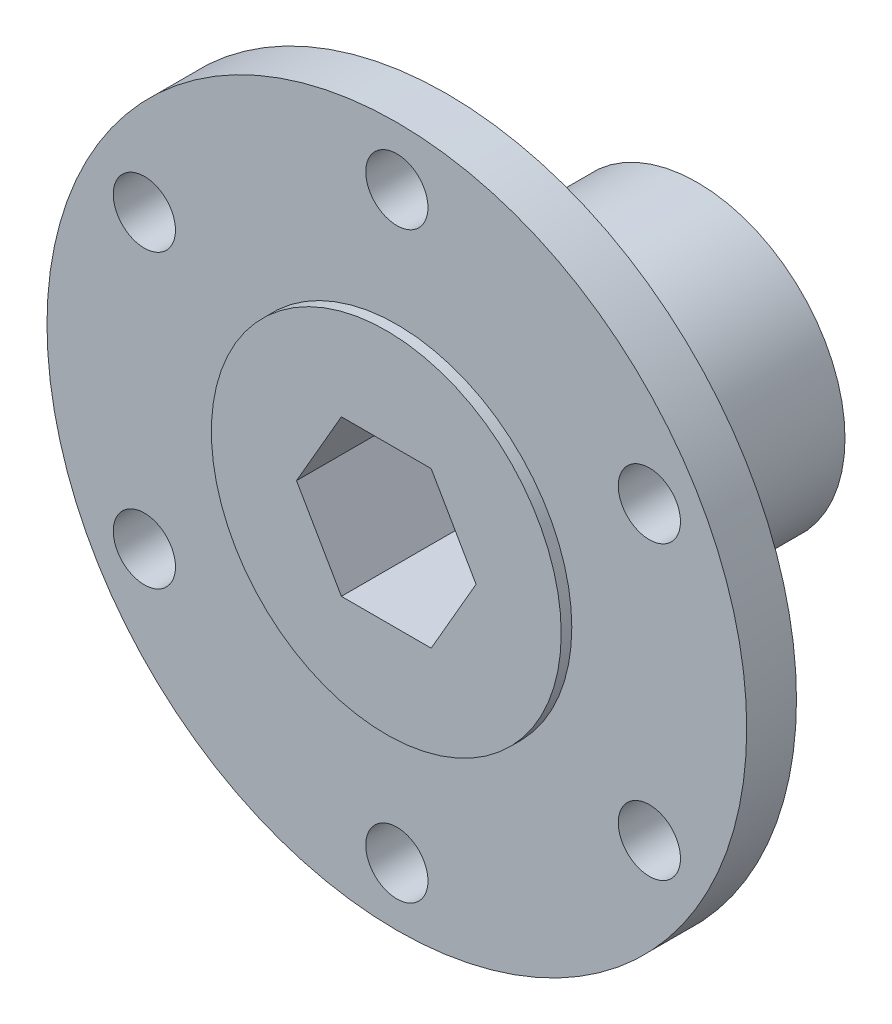
SolidWorks part; units mm, degrees
ref_plane "Front Plane" through (0, 0, 0) normal (0, 0, 1) x (1, 0, 0)
ref_plane "Top Plane" through (0, 0, 0) normal (0, 1, 0) x (1, 0, 0)
ref_plane "Right Plane" through (0, 0, 0) normal (1, 0, 0) x (0, 0, -1)
sketch "Sketch1" plane through (0, 0, 0) normal (0, 0, 1) x (1, 0, 0)
  line L0 (0, 0) -> (0, 23.8125) construction
  line L1 (7.3323, 0) -> (3.6662, 6.35)
  line L2 (3.6662, 6.35) -> (-3.6662, 6.35)
  line L3 (-3.6662, 6.35) -> (-7.3323, 0)
  line L4 (-7.3323, 0) -> (-3.6662, -6.35)
  line L5 (-3.6662, -6.35) -> (3.6662, -6.35)
  line L6 (3.6662, -6.35) -> (7.3323, 0)
  circle A0 centre (0, 0) radius 28.575
  circle A1 centre (0, 0) radius 6.35 construction
  circle A2 centre (0, 23.8125) radius 2.54
  circle A3 centre (20.6222, 11.9063) radius 2.54
  circle A4 centre (20.6222, -11.9062) radius 2.54
  circle A5 centre (0, -23.8125) radius 2.54
  circle A6 centre (-20.6222, -11.9063) radius 2.54
  circle A7 centre (-20.6222, 11.9062) radius 2.54
  point P24 (0, 0)
  dimension "D1" = 57.15
  dimension "D2" = 12.7
  dimension "D4" = 5.08
  dimension "D3" = 23.8125
  dimension "D5" = 6
extrude "Boss-Extrude1" add sketch "Sketch1" along normal blind 4.064
sketch "Sketch2" plane through (0, 0, 4.064) normal (0, 0, 1) x (1, 0, 0)
  line L13 (3.6662, -6.35) -> (7.3323, 0)
  line L14 (7.3323, 0) -> (3.6662, 6.35)
  line L15 (3.6662, 6.35) -> (-3.6662, 6.35)
  line L16 (-3.6662, 6.35) -> (-7.3323, 0)
  line L17 (-7.3323, 0) -> (-3.6662, -6.35)
  line L18 (-3.6662, -6.35) -> (3.6662, -6.35)
  circle A0 centre (0, 0) radius 14.2875
  circle A1 centre (0, 0) radius 6.35 construction
  circle A2 centre (0, 0) radius 28.575
  circle A3 centre (0, 0) radius 28.575
  line M4 (3.6662, 6.35) -> (7.3323, 0)
  line M5 (7.3323, 0) -> (3.6662, -6.35)
  line M6 (3.6662, -6.35) -> (-3.6662, -6.35)
  line M7 (-3.6662, -6.35) -> (-7.3323, 0)
  line M8 (-7.3323, 0) -> (-3.6662, 6.35)
  line M9 (-3.6662, 6.35) -> (3.6662, 6.35)
  dimension "D1" = 28.575
  dimension "D2" = 0
extrude "Boss-Extrude2" add sketch "Sketch2" along normal blind 0.8636 contours A0 M9 M4 M5 M6 M7 M8
sketch "Sketch3" plane through (0, 0, 0) normal (0, 0, -1) x (-1, 0, 0)
  line L1 (7.3323, 0) -> (3.6662, 6.35)
  line L2 (3.6662, 6.35) -> (-3.6662, 6.35)
  line L3 (-3.6662, 6.35) -> (-7.3323, 0)
  line L4 (-7.3323, 0) -> (-3.6662, -6.35)
  line L5 (-3.6662, -6.35) -> (3.6662, -6.35)
  line L6 (3.6662, -6.35) -> (7.3323, 0)
  circle A0 centre (0, 0) radius 12.065
  circle A1 centre (0, 0) radius 6.35 construction
  dimension "D1" = 24.13
extrude "m" add sketch "Sketch3" along normal blind 20.4724
